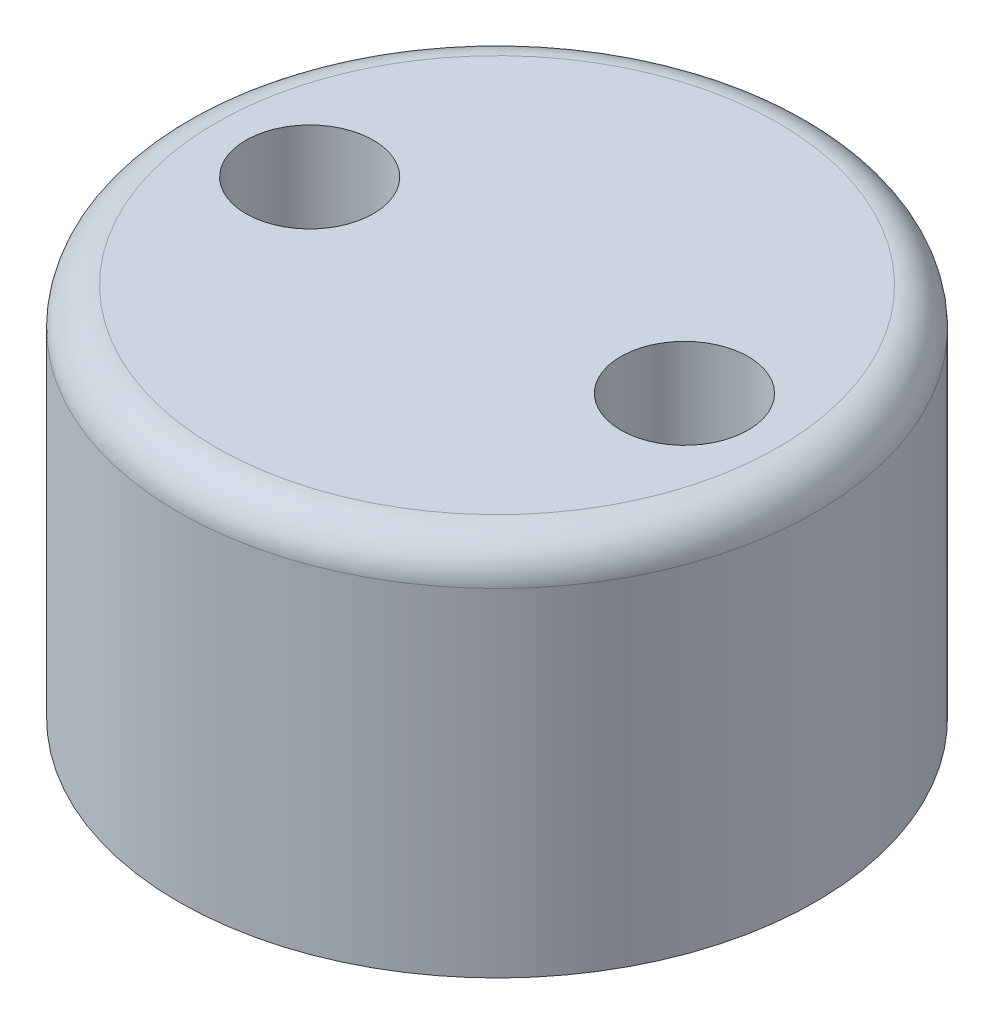
SolidWorks part; units mm, degrees
ref_plane "Front Plane" through (0, 0, 0) normal (0, 0, 1) x (1, 0, 0)
ref_plane "Top Plane" through (0, 0, 0) normal (0, 1, 0) x (1, 0, 0)
ref_plane "Right Plane" through (0, 0, 0) normal (1, 0, 0) x (0, 0, -1)
sketch "Sketch1" plane through (0, 0, 0) normal (0, 1, 0) x (1, 0, 0)
  circle A0 centre (0, 0) radius 8.5
extrude "Boss-Extrude1" add sketch "Sketch1" along normal blind 10 contours A0
fillet "Fillet2" radius 1 1 edges at (0, 10, 8.5)
hole_wizard "M3 Clearance Hole1" positions "Sketch4" profile "Sketch5" hole size "M3" standard "ANSI Metric" end condition through all
sketch "Sketch4" plane through (0, 10, 0) normal (0, 1, 0) x (1, 0, 0)
  point P0 (-5, 0)
  point P3 (5, 0)
  point P8 (0, 0)
  point P9 (0, 0)
sketch "Sketch5" plane through (-5, 10, 0) normal (1, 0, 0) x (0, 0, 1)
  line L0 (0, 0) -> (0, 10)
  line L1 (0, 10) -> (1.7, 10)
  line L2 (1.7, 10) -> (1.7, 0)
  line L5 (1.7, 0) -> (0, 0)
  line L11 (0, -6.35) -> (0, 107.95) construction
  dimension "Thru Hole Dia." = 3.4
  dimension "Thru Hole Depth" = 10
